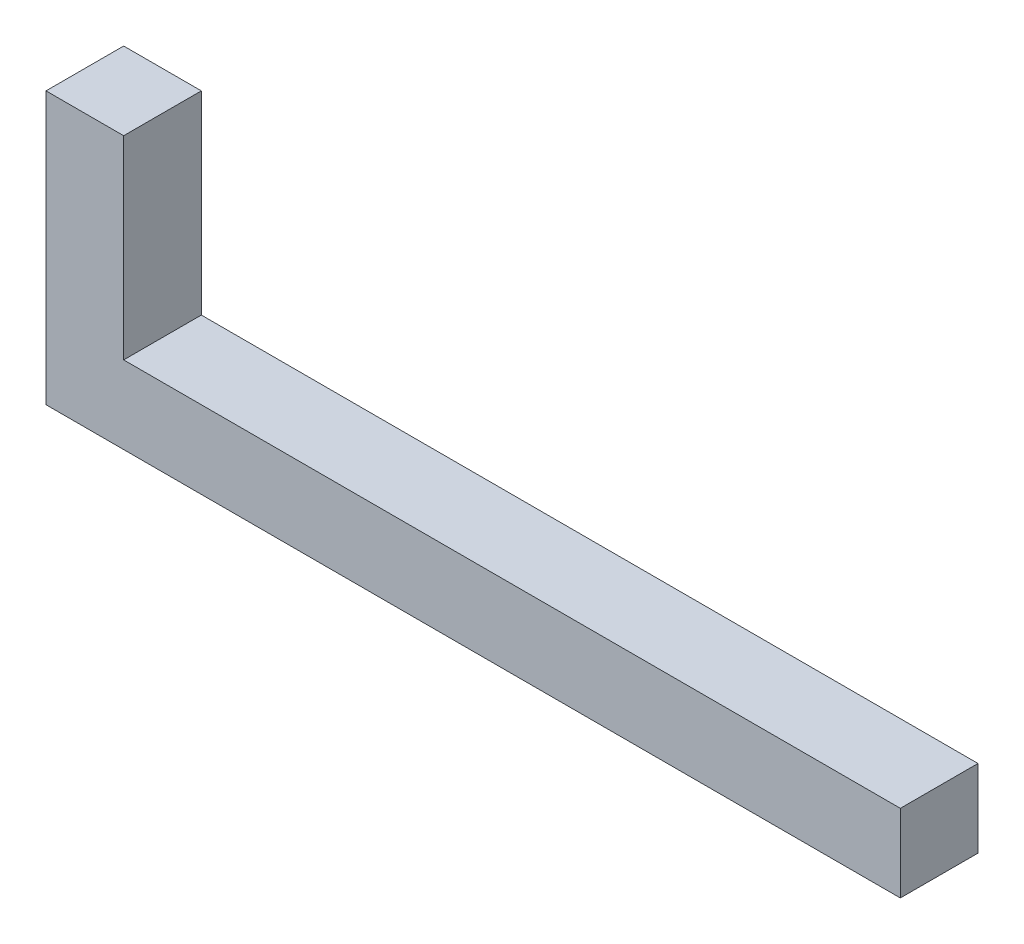
SolidWorks part; units mm, degrees
ref_plane "Front Plane" through (0, 0, 0) normal (0, 0, 1) x (1, 0, 0)
ref_plane "Top Plane" through (0, 0, 0) normal (0, 1, 0) x (1, 0, 0)
ref_plane "Right Plane" through (0, 0, 0) normal (1, 0, 0) x (0, 0, -1)
sketch "Sketch1" plane through (0, 0, 0) normal (0, 0, 1) x (1, 0, 0)
  line L0 (0, 0) -> (-100, 0)
  line L1 (-100, 0) -> (-100, 25)
  line L2 (0, 0) -> (0, -10)
  line L3 (0, -10) -> (-110, -10)
  line L4 (-110, -10) -> (-110, 25)
  line L5 (-110, 25) -> (-100, 25)
  dimension "D1" = 100
  dimension "D2" = 10
  dimension "D3" = 110
  dimension "D4" = 25
extrude "Boss-Extrude1" add sketch "Sketch1" along normal blind 10
